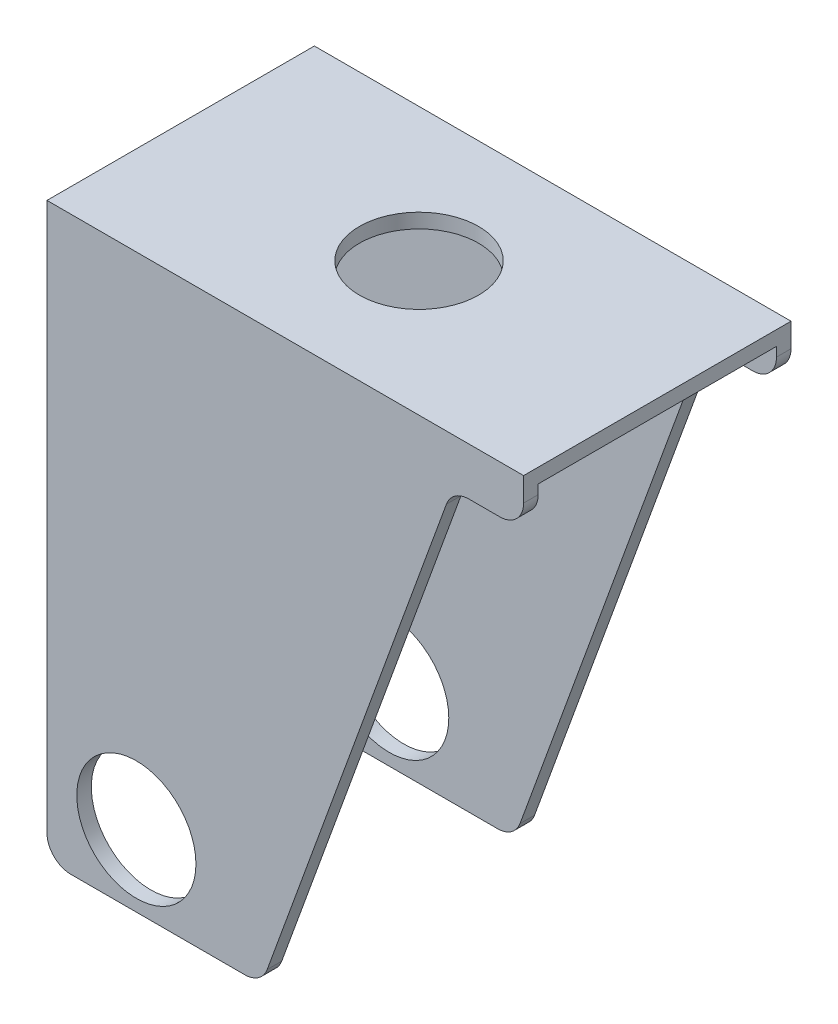
SolidWorks part; units mm, degrees
material "6061-T6 (SS)"
ref_plane "Front Plane" through (0, 0, 0) normal (0, 0, 1) x (1, 0, 0)
ref_plane "Top Plane" through (0, 0, 0) normal (0, 1, 0) x (1, 0, 0)
ref_plane "Right Plane" through (0, 0, 0) normal (1, 0, 0) x (0, 0, -1)
sketch "Sketch1" plane through (0, 0, 0) normal (1, 0, 0) x (0, 0, -1)
  line L0 (12.7, 0) -> (14.2494, 0)
  line L1 (14.2494, 0) -> (14.2494, 60.9346)
  line L2 (14.2494, 60.9346) -> (-14.2494, 60.9346)
  line L3 (-14.2494, 60.9346) -> (-14.2494, 0)
  line L4 (-14.2494, 0) -> (-12.7, 0)
  line L5 (-12.7, 0) -> (-12.7, 59.3852)
  line L6 (-12.7, 59.3852) -> (12.7, 59.3852)
  line L7 (12.7, 59.3852) -> (12.7, 0)
  dimension "D1" = 1.5494
  dimension "D2" = 25.4
  dimension "D3" = 12.7
  dimension "D4" = 1.5494
  dimension "D5" = 60.9346
extrude "Boss-Extrude1" add sketch "Sketch1" along normal blind 50.8
sketch "Sketch2" plane through (0, 0, 14.2494) normal (0, 0, 1) x (1, 0, 0)
  line L0 (50.8, 0) -> (0, 0) construction
  line L1 (0, 60.9346) -> (0, 0) construction
  line L2 (22.86, 0) -> (50.8, 0)
  line L3 (50.8, 0) -> (50.8, 55.8546)
  line L4 (50.8, 60.9346) -> (50.8, 0) construction
  line L7 (50.8, 55.8546) -> (43.18, 55.8546)
  line L8 (43.18, 55.8546) -> (22.86, 0)
  line L9 (50.8, 60.9346) -> (0, 60.9346) construction
  circle A0 centre (9.525, 7.62) radius 6.35
  circle A1 centre (9.525, 7.62) radius 38.1 construction
  dimension "D1" = 76.2
  dimension "D2" = 12.7
  dimension "D6" = 27.94
  dimension "D3" = 7.62
  dimension "D4" = 9.525
  dimension "D5" = 5.08
  dimension "D7" = 7.62
extrude "Cut-Extrude1" cut sketch "Sketch2" against normal through all
fillet "Fillet1" radius 2.54 8 edges at (0, 0, -13.4747) (22.86, 0, -13.4747) (50.8, 55.8546, -13.4747) (43.18, 55.8546, -13.4747) (50.8, 55.8546, 13.4747) (43.18, 55.8546, 13.4747) (0, 0, 13.4747) (22.86, 0, 13.4747)
sketch "Sketch3" plane through (0, 60.9346, 0) normal (0, 1, 0) x (1, 0, 0)
  line L0 (25.4, 14.2494) -> (25.4, -14.2494) construction
  line L1 (50.8, 14.2494) -> (0, 14.2494) construction
  line L2 (50.8, -14.2494) -> (0, -14.2494) construction
  circle A0 centre (25.4, 0) radius 6.35
  dimension "D1" = 12.7
extrude "Cut-Extrude2" cut sketch "Sketch3" against normal up to next
